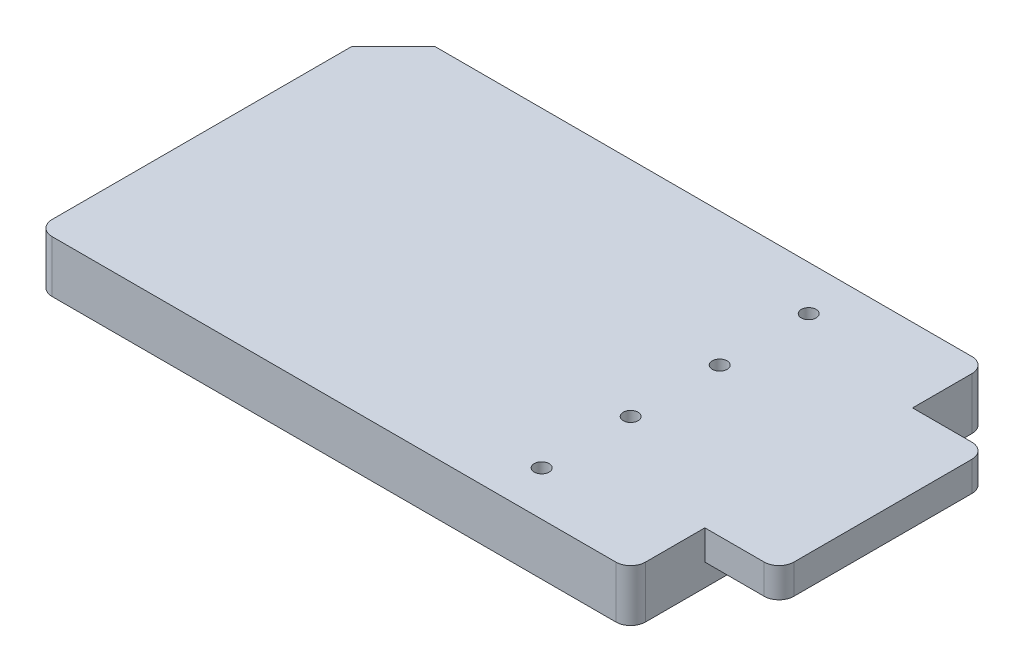
SolidWorks part; units mm, degrees
ref_plane "Front Plane" through (0, 0, 0) normal (0, 0, 1) x (1, 0, 0)
ref_plane "Top Plane" through (0, 0, 0) normal (0, 1, 0) x (1, 0, 0)
ref_plane "Right Plane" through (0, 0, 0) normal (1, 0, 0) x (0, 0, -1)
sketch "Sketch4" plane through (0, 0, 0) normal (0, 1, 0) x (1, 0, 0)
  line L1 (0, -12) -> (40, -12)
  line L2 (0, -12) -> (0, 12)
  line L3 (0, 12) -> (40, 12)
  line L4 (40, -12) -> (40, 12)
  point P4 (0, 0)
  dimension "D1" = 40
  dimension "D2" = 24
extrude "Boss-Extrude2" add sketch "Sketch4" along normal blind 3.5
fillet "Fillet2" radius 1 3 edges at (0, 1.75, 12) (40, 1.75, -12) (40, 1.75, 12)
sketch "Sketch5" plane through (0, 3.5, 0) normal (0, 1, 0) x (1, 0, 0)
  line L0 (40, -11) -> (40, 11) construction
  line L1 (40, 7) -> (45, 7)
  line L2 (40, 7) -> (40, -7)
  line L3 (40, -7) -> (45, -7)
  line L4 (45, 7) -> (45, -7)
  point P6 (45, 0)
  dimension "D1" = 5
  dimension "D2" = 14
extrude "Boss-Extrude3" add sketch "Sketch5" against normal blind 2
fillet "Fillet3" radius 1 2 edges at (45, 2.5, 7) (45, 2.5, -7)
chamfer "Chamfer1" distance 2.8 angle 45 1 edges at (0, 1.75, -12)
sketch "Sketch6" plane through (0, 0, 0) normal (-1, 0, 0) x (0, 0, 1)
  line L0 (-9.2, 0) -> (11, 0) construction
  circle A0 centre (0, 1.75) radius 1.15
  dimension "D1" = 2.3
  dimension "D2" = 1.75
extrude "Cut-Extrude1" cut sketch "Sketch6" against normal blind 5
sketch "Sketch8" plane through (0, 0, 0) normal (0, -1, 0) x (1, 0, 0)
  circle A0 centre (5, 0) radius 0.6
  dimension "D1" = 1.2
  dimension "D2" = 5
extrude "Cut-Extrude2" cut sketch "Sketch8" against normal blind 1.75
sketch "Sketch9" plane through (0, 0, 0) normal (0, -1, 0) x (1, 0, 0)
  circle A0 centre (7, 0) radius 3.5
  dimension "D1" = 7
  dimension "D2" = 7
extrude "Cut-Extrude3" cut sketch "Sketch9" against normal blind 1.5
sketch "Sketch10" plane through (0, 0, 0) normal (0, -1, 0) x (1, 0, 0)
  circle A0 centre (7, -7) radius 3
  dimension "D3" = 6
  dimension "D1" = 7
  dimension "D2" = 7
extrude "Cut-Extrude4" cut sketch "Sketch10" against normal blind 1
sketch "Sketch11" plane through (0, 0, 0) normal (0, -1, 0) x (-1, 0, 0)
  line L0 (-7, 7) -> (-7, 3.5) construction
  line L1 (-6.5, 7) -> (-6.5, 3.5)
  line L2 (-7.5, 7) -> (-7.5, 3.5)
  line L4 (0, 9.2) -> (0, -11) construction
  line L5 (-20, 0) -> (-7, 0) construction
  line L6 (-20, 0.5) -> (-7, 0.5)
  line L7 (-20, -0.5) -> (-7, -0.5)
  arc A0 (-6.5, 7) -> (-7.5, 7) centre (-7, 7) ccw
  arc A1 (-7.5, 3.5) -> (-6.5, 3.5) centre (-7, 3.5) ccw
  arc A2 (-20, 0.5) -> (-20, -0.5) centre (-20, 0) ccw
  arc A3 (-7, -0.5) -> (-7, 0.5) centre (-7, 0) ccw
  point P2 (-7, 5.25)
  point P7 (-13.5, 0)
  dimension "D4" = 0.5
  dimension "D7" = 0.5
  dimension "D1" = 7
  dimension "D2" = 7
  dimension "D3" = 3.5
  dimension "D5" = 7
  dimension "D6" = 13
extrude "Cut-Extrude5" cut sketch "Sketch11" against normal blind 0.8
sketch "Sketch12" plane through (0, 0, 0) normal (0, -1, 0) x (1, 0, 0)
  circle A0 centre (14, 0) radius 2.5
  dimension "D1" = 5
  dimension "D2" = 14
extrude "Cut-Extrude6" cut sketch "Sketch12" against normal blind 1
sketch "Sketch14" plane through (0, 0, 0) normal (0, -1, 0) x (1, 0, 0)
  line L0 (20, -9) -> (20, 9) construction
  line L1 (19.5, -9) -> (19.5, 9)
  line L2 (20.5, -9) -> (20.5, 9)
  arc A0 (19.5, -9) -> (20.5, -9) centre (20, -9) ccw
  arc A1 (20.5, 9) -> (19.5, 9) centre (20, 9) ccw
  point P2 (20, 0)
  dimension "D3" = 0.5
  dimension "D1" = 20
  dimension "D2" = 18
extrude "Cut-Extrude7" cut sketch "Sketch14" against normal blind 0.8
sketch "Sketch15" plane through (0, 0, 0) normal (0, -1, 0) x (1, 0, 0)
  line L0 (20, -9) -> (24, -9) construction
  line L1 (20, -8.5) -> (24, -8.5)
  line L2 (20, -9.5) -> (24, -9.5)
  arc A0 (20, -8.5) -> (20, -9.5) centre (20, -9) ccw
  arc A1 (24, -9.5) -> (24, -8.5) centre (24, -9) ccw
  point P2 (22, -9)
  dimension "D2" = 0.5
  dimension "D1" = 4
extrude "Cut-Extrude8" cut sketch "Sketch15" against normal blind 0.8
sketch "Sketch16" plane through (0, 0, 0) normal (0, -1, 0) x (1, 0, 0)
  circle A0 centre (24, -9) radius 2.25
  dimension "D1" = 4.5
extrude "Cut-Extrude9" cut sketch "Sketch16" against normal blind 1.5
sketch "Sketch17" plane through (0, 0, 0) normal (0, -1, 0) x (1, 0, 0)
  line L0 (31, -9) -> (24, -9) construction
  line L1 (31, -9.3) -> (24, -9.3)
  line L2 (31, -8.7) -> (24, -8.7)
  arc A0 (31, -9.3) -> (31, -8.7) centre (31, -9) ccw
  arc A1 (24, -8.7) -> (24, -9.3) centre (24, -9) ccw
  point P3 (27.5, -9)
  dimension "D1" = 7
  dimension "D2" = 0.6
extrude "Cut-Extrude10" cut sketch "Sketch17" against normal blind 0.5
sketch "Sketch18" plane through (0, 0, 0) normal (0, -1, 0) x (-1, 0, 0)
  circle A0 centre (-31, 9) radius 0.5
  dimension "D1" = 1
extrude "Cut-Extrude11" cut sketch "Sketch18" against normal through all
pattern_linear "LPattern3" count 4 spacing 6 along (0, 0, 1) of "Cut-Extrude11", "Cut-Extrude10", "Cut-Extrude9", "Cut-Extrude8"
